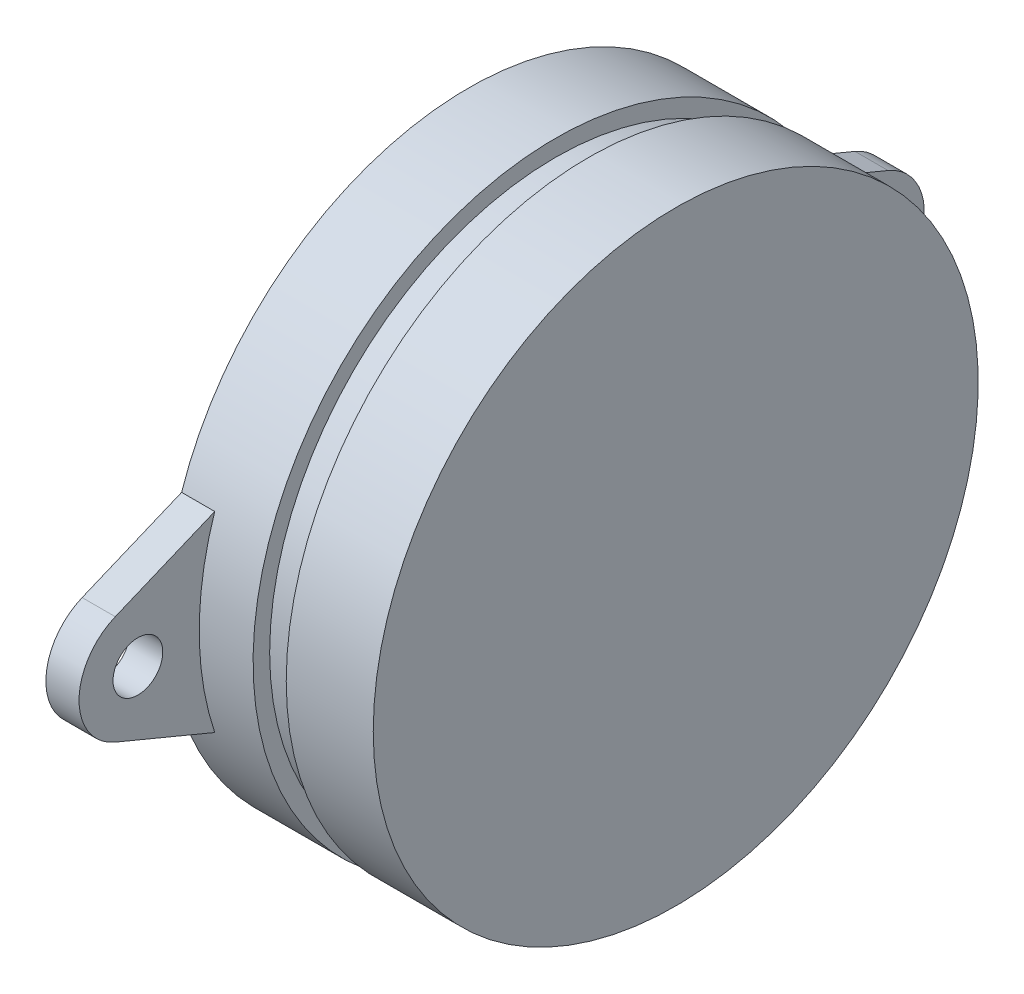
SolidWorks part; units mm, degrees
ref_plane "Plan de face" through (0, 0, 0) normal (0, 0, 1) x (1, 0, 0)
ref_plane "Plan de dessus" through (0, 0, 0) normal (0, 1, 0) x (1, 0, 0)
ref_plane "Plan de droite" through (0, 0, 0) normal (1, 0, 0) x (0, 0, -1)
sketch "Esquisse2" plane through (0, 0, 0) normal (1, 0, 0) x (0, 0, -1)
  circle A0 centre (0, 0) radius 18.25
  dimension "D1" = 36.5
extrude "Boss.-Extru.1" add sketch "Esquisse2" along normal blind 5.25
sketch "Esquisse3" plane through (5.25, 0, 0) normal (1, 0, 0) x (0, 0, -1)
  circle A0 centre (0, 0) radius 17.25
  dimension "D1" = 34.5
extrude "Boss.-Extru.2" add sketch "Esquisse3" along normal blind 2
sketch "Esquisse4" plane through (7.25, 0, 0) normal (1, 0, 0) x (0, 0, -1)
  circle A0 centre (0, 0) radius 18.25
  dimension "D1" = 36.5
extrude "Boss.-Extru.3" add sketch "Esquisse4" along normal blind 5.25
sketch "Esquisse6" plane through (0, 0, 0) normal (-1, 0, 0) x (0, 0, 1)
  line L0 (0, 0) -> (21.95, 0) construction
  line L1 (0, 0) -> (0, 18.25) construction
  line L2 (21.95, 0) -> (23.3137, 3.2776) construction
  line L3 (21.95, 0) -> (25.5, 0) construction
  line L4 (23.3137, 3.2776) -> (17.3124, 5.7745)
  line L5 (23.3137, -3.2776) -> (17.3124, -5.7745)
  line L6 (-23.3137, 3.2776) -> (-17.3124, 5.7745)
  line L7 (-23.3137, -3.2776) -> (-17.3124, -5.7745)
  circle A0 centre (0, 0) radius 18.25 construction
  circle A1 centre (21.95, 0) radius 1.5
  arc A2 (23.3137, 3.2776) -> (23.3137, -3.2776) centre (21.95, 0) cw
  arc A3 (17.3124, 5.7745) -> (17.294, -5.8292) centre (0, 0) cw
  circle A4 centre (-21.95, 0) radius 1.5
  arc A5 (-23.3137, 3.2776) -> (-23.3137, -3.2776) centre (-21.95, 0) ccw
  arc A6 (-17.3124, 5.7745) -> (-17.294, -5.8292) centre (0, 0) ccw
  circle M5 centre (0, 0) radius 18.25
  dimension "D3" = 3
  dimension "D1" = 21.95
  dimension "D2" = 25.5
  dimension "D4" = 6.5
extrude "Boss.-Extru.4" add sketch "Esquisse6" against normal blind 2 contours A2 L4 L5 A1 M5 | L6 A5 L7 A4 M5
sketch "Esquisse7" plane through (0, 0, 0) normal (-1, 0, 0) x (0, 0, 1)
  circle A0 centre (0, 0) radius 8
  dimension "D1" = 16
extrude "Boss.-Extru.5" add sketch "Esquisse7" along normal blind 2
sketch "Esquisse8" plane through (0, 0, 0) normal (-1, 0, 0) x (0, 0, 1)
  circle A0 centre (0, 0) radius 2.5
  dimension "D1" = 5
extrude "Boss.-Extru.6" add sketch "Esquisse8" along normal blind 10.5
chamfer "Chanfrein1" distance 0.25 angle 45 1 edges at (-10.5, 0, 2.5)
sketch "Esquisse9" plane through (-10.5, 0, 0) normal (-1, 0, 0) x (0, 0, 1)
  line L1 (-2.5, 2) -> (2.5, 2)
  line L2 (-2.5, 2) -> (-2.5, 3)
  line L3 (-2.5, 3) -> (2.5, 3)
  line L4 (2.5, 2) -> (2.5, 3)
  dimension "D1" = 5
  dimension "D2" = 2.5
  dimension "D3" = 2
  dimension "D4" = 1
extrude "Enlèv. mat.-Extru.1" cut sketch "Esquisse9" against normal blind 5
